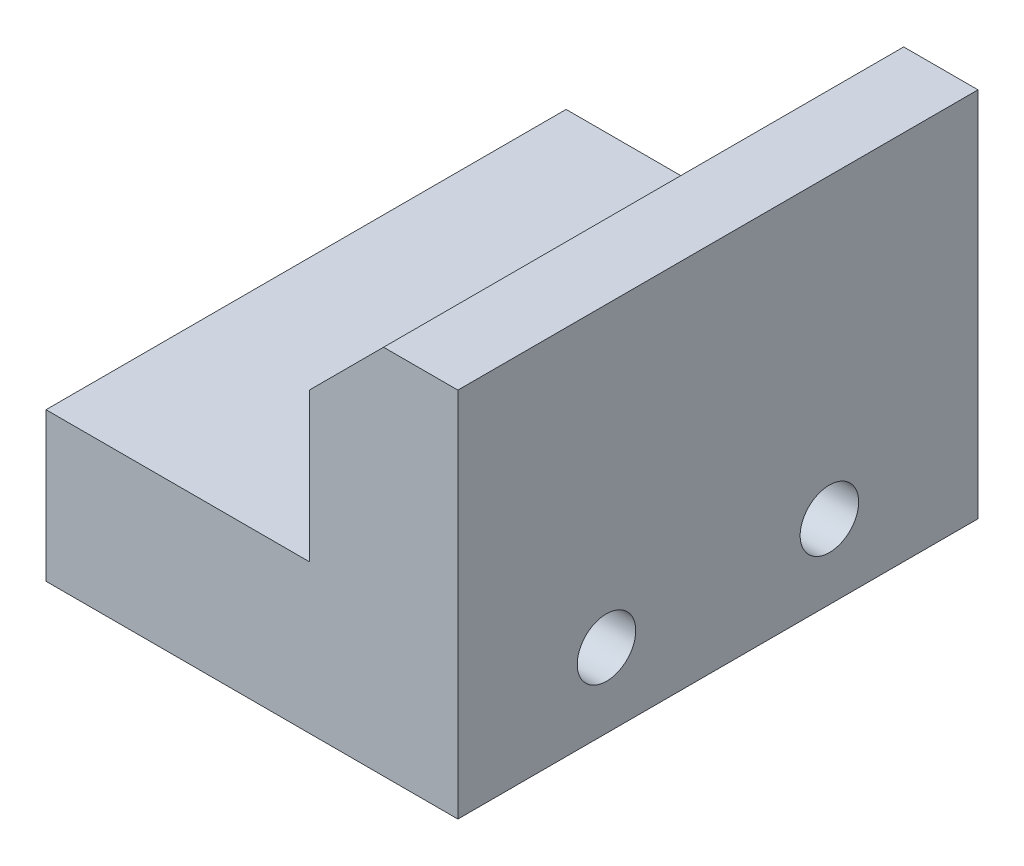
SolidWorks part; units mm, degrees
material "PETG"
ref_plane "Front Plane" through (0, 0, 0) normal (0, 0, 1) x (1, 0, 0)
ref_plane "Top Plane" through (0, 0, 0) normal (0, 1, 0) x (1, 0, 0)
ref_plane "Right Plane" through (0, 0, 0) normal (1, 0, 0) x (0, 0, -1)
sketch "Sketch1" plane through (0, 0, 0) normal (0, 0, 1) x (1, 0, 0)
  line L0 (70.4, 63.5) -> (45, 38.1)
  line L1 (0, -12.7) -> (70.4, -12.7)
  line L2 (0, -12.7) -> (0, 12.7)
  line L3 (0, 12.7) -> (45, 12.7)
  line L5 (45, 63.5) -> (70.4, 63.5)
  line L6 (45, 63.5) -> (45, 12.7)
  line L8 (70.4, 63.5) -> (70.4, -12.7)
  line L9 (57.7, 50.8) -> (70.4, 50.8)
  dimension "D1" = 25.4
  dimension "D2" = 70.4
  dimension "D3" = 25.4
  dimension "D4" = 50.8
  dimension "D5" = 25.4
  dimension "D6" = 12.7
extrude "Boss-Extrude1" add sketch "Sketch1" along normal mid plane 88.9 contours L8 L0 L6 L3 L2 L1
sketch "Sketch2" plane through (70.4, 0, 0) normal (1, 0, 0) x (0, 0, -1)
  line L0 (-19.05, 0) -> (0, 0) construction
  line L1 (0, 0) -> (19.05, 0) construction
  line L2 (-44.45, 50.8) -> (-44.45, -12.7) construction
  circle A0 centre (-19.05, 0) radius 2.8
  circle A1 centre (19.05, 0) radius 2.8
  dimension "D1" = 5.6
  dimension "D2" = 25.4
extrude "Cut-Extrude1" cut sketch "Sketch2" against normal through all
sketch "Sketch3" plane through (70.4, 0, 0) normal (1, 0, 0) x (0, 0, -1)
  circle A0 centre (-19.05, 0) radius 5
  circle A1 centre (19.05, 0) radius 5
  dimension "D1" = 10
extrude "Cut-Extrude2" cut sketch "Sketch3" against normal offset from surface (60.4 mm away) 10 up to face at (0, 0, 16.25)
equation "\"D2@Sketch1\"= 45mm + 1in"
